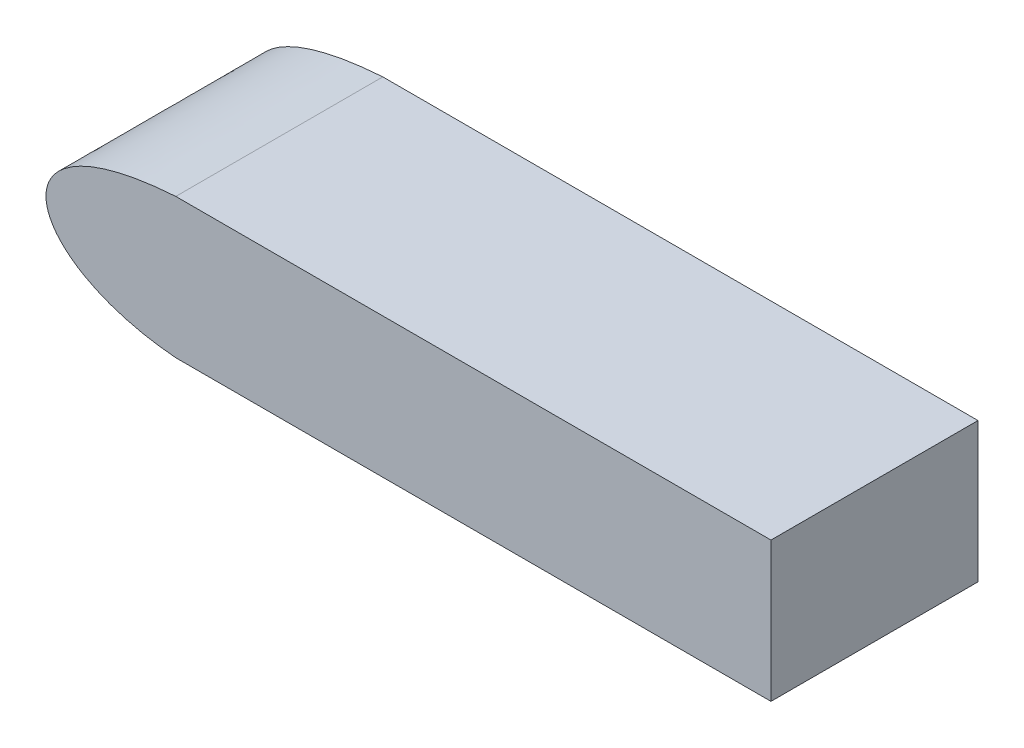
SolidWorks part; units mm, degrees
ref_plane "Front Plane" through (0, 0, 0) normal (0, 0, 1) x (1, 0, 0)
ref_plane "Top Plane" through (0, 0, 0) normal (0, 1, 0) x (1, 0, 0)
ref_plane "Right Plane" through (0, 0, 0) normal (1, 0, 0) x (0, 0, -1)
sketch "Sketch1" plane through (0, 0, 0) normal (0, 0, 1) x (1, 0, 0)
  line L1 (0, 0) -> (115, 0)
  line L3 (0, 27) -> (115, 27)
  line L4 (115, 0) -> (115, 27)
  spline S0 degree 3 poles (0, 0) (-29.6009, 2.4506) (-37.0658, 24.5494) (0, 27) knots 0 0 0 0 1 1 1 1
  point P5 (-25, 13.5)
  dimension "D1" = 115
  dimension "D2" = 27
  dimension "D4" = 13.5
extrude "Boss-Extrude1" add sketch "Sketch1" against normal blind 40
